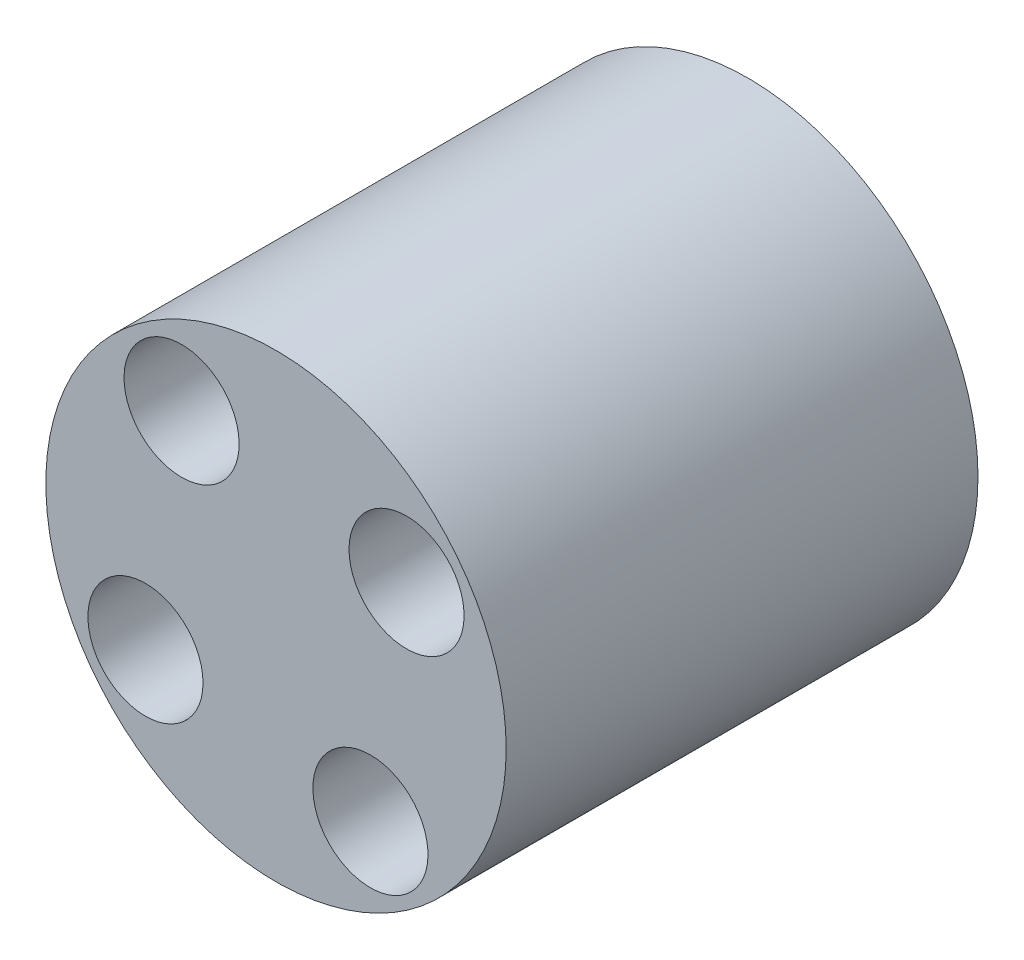
SolidWorks part; units mm, degrees
ref_plane "Front Plane" through (0, 0, 0) normal (0, 0, 1) x (1, 0, 0)
ref_plane "Top Plane" through (0, 0, 0) normal (0, 1, 0) x (1, 0, 0)
ref_plane "Right Plane" through (0, 0, 0) normal (1, 0, 0) x (0, 0, -1)
sketch "Sketch2" plane through (0, 0, 0) normal (0, 0, 1) x (1, 0, 0)
  circle A0 centre (0, 0) radius 20
extrude "Boss-Extrude1" add sketch "Sketch2" along normal blind 35
sketch "Sketch5" plane through (0, 0, 35) normal (0, 0, 1) x (1, 0, 0)
  circle A0 centre (0, 0) radius 20
extrude "Boss-Extrude4" add sketch "Sketch5" along normal blind 6
sketch "Sketch6" plane through (0, 0, 0) normal (0, 0, -1) x (-1, 0, 0)
  circle A0 centre (-11.3434, 8.2053) radius 5
  point P2 (0, 0)
  dimension "D1" = 14
extrude "Cut-Extrude1" cut sketch "Sketch6" against normal through all
pattern_circular "CirPattern2" count 4 over 360 about axis through (0, 0, 0) along (0, 0, 1) of "Cut-Extrude1"
